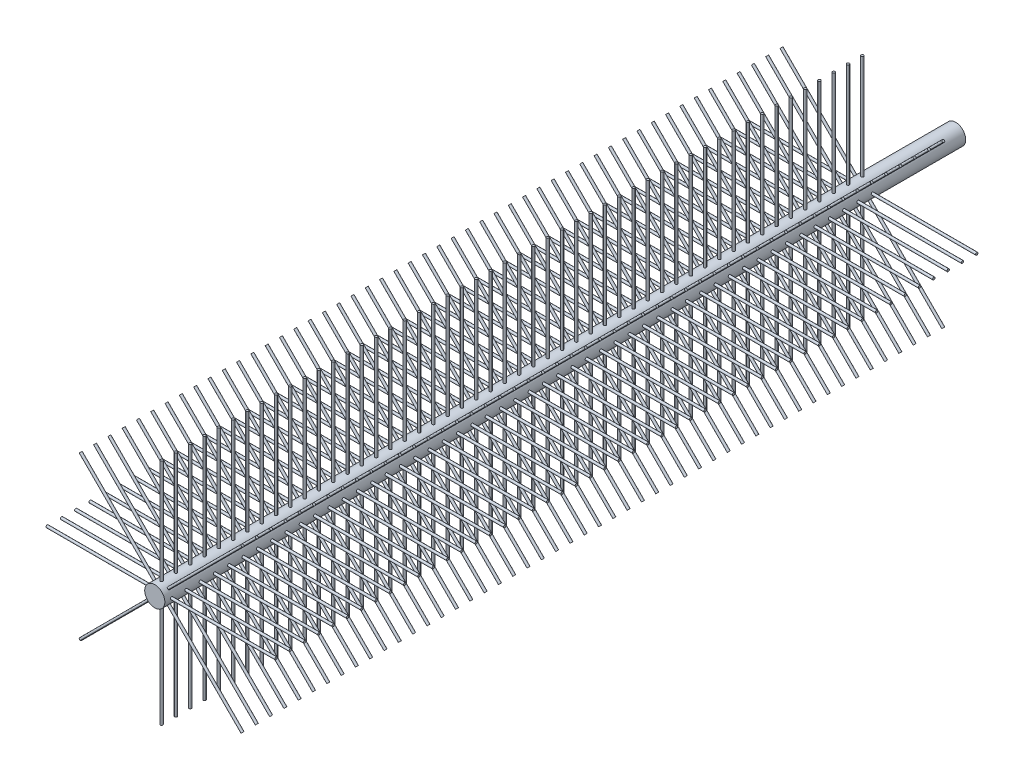
SolidWorks part; units mm, degrees
ref_plane "Front Plane" through (0, 0, 0) normal (0, 0, 1) x (1, 0, 0)
ref_plane "Top Plane" through (0, 0, 0) normal (0, 1, 0) x (1, 0, 0)
ref_plane "Right Plane" through (0, 0, 0) normal (1, 0, 0) x (0, 0, -1)
sketch "Sketch1" plane through (0, 0, 0) normal (0, 0, 1) x (1, 0, 0)
  circle A0 centre (0, 0) radius 1.7613
extrude "Boss-Extrude1" add sketch "Sketch1" against normal blind 140
sketch "Sketch2" plane through (0, 0, 0) normal (1, 0, 0) x (0, 0, -1)
  circle A0 centre (1.1989, 0) radius 0.2146
extrude "Boss-Extrude3" add sketch "Sketch2" along normal blind 20 separate body
sketch "Sketch3" plane through (0, 0, 0) normal (0, 0, 1) x (1, 0, 0)
  circle A0 centre (0, 0) radius 0.4658
  dimension "D1" = 0.9316
pattern_circular "CirPattern8" count 8 over 360 about axis through (0, 0, 0) along (0, 0, 1) of bodies 105
combine bodies "Combine1" bodies to combine 105 106 107 108 109 110 111 112
pattern_linear "LPattern2" count 50 spacing 2.5 along (0, 0, -1) of bodies 113
